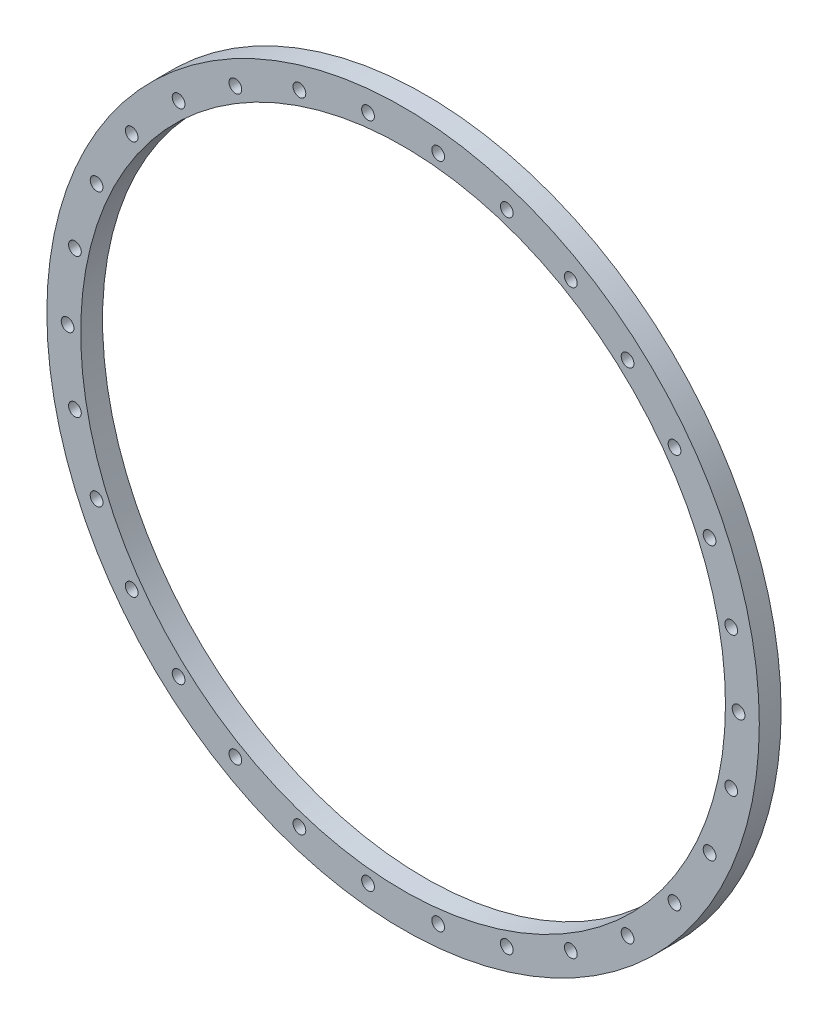
SolidWorks part; units mm, degrees
ref_plane "Plan de face" through (0, 0, 0) normal (0, 0, 1) x (1, 0, 0)
ref_plane "Plan de dessus" through (0, 0, 0) normal (0, 1, 0) x (1, 0, 0)
ref_plane "Plan de droite" through (0, 0, 0) normal (1, 0, 0) x (0, 0, -1)
sketch "Esquisse1" plane through (0, 0, 0) normal (0, 0, 1) x (1, 0, 0)
  line L0 (0, 0) -> (-461, 0) construction
  line L1 (0, 0) -> (-450.926, 95.8473) construction
  circle A0 centre (0, 0) radius 443
  circle A1 centre (0, 0) radius 489.5
  circle A2 centre (-461, 0) radius 8.75
  circle A3 centre (-450.926, 95.8473) radius 8.75
  circle A4 centre (-421.1445, 187.5056) radius 8.75
  circle A5 centre (-372.9568, 270.969) radius 8.75
  circle A6 centre (-308.4692, 342.5898) radius 8.75
  circle A7 centre (-230.5, 399.2377) radius 8.75
  circle A8 centre (-142.4568, 438.4371) radius 8.75
  circle A9 centre (-48.1876, 458.4746) radius 8.75
  circle A10 centre (48.1876, 458.4746) radius 8.75
  circle A11 centre (142.4568, 438.4371) radius 8.75
  circle A12 centre (230.5, 399.2377) radius 8.75
  circle A13 centre (308.4692, 342.5898) radius 8.75
  circle A14 centre (372.9568, 270.969) radius 8.75
  circle A15 centre (421.1445, 187.5056) radius 8.75
  circle A16 centre (450.926, 95.8473) radius 8.75
  circle A17 centre (461, 0) radius 8.75
  circle A18 centre (450.926, -95.8473) radius 8.75
  circle A19 centre (421.1445, -187.5056) radius 8.75
  circle A20 centre (372.9568, -270.969) radius 8.75
  circle A21 centre (308.4692, -342.5898) radius 8.75
  circle A22 centre (230.5, -399.2377) radius 8.75
  circle A23 centre (142.4568, -438.4371) radius 8.75
  circle A24 centre (48.1876, -458.4746) radius 8.75
  circle A25 centre (-48.1876, -458.4746) radius 8.75
  circle A26 centre (-142.4568, -438.4371) radius 8.75
  circle A27 centre (-230.5, -399.2377) radius 8.75
  circle A28 centre (-308.4692, -342.5898) radius 8.75
  circle A29 centre (-372.9568, -270.969) radius 8.75
  circle A30 centre (-421.1445, -187.5056) radius 8.75
  circle A31 centre (-450.926, -95.8473) radius 8.75
  circle A32 centre (0, 0) radius 461 construction
  point P67 (0, 0)
  dimension "D1" = 979
  dimension "D2" = 886
  dimension "D3" = 17.5
  dimension "D4" = 461
  dimension "D5" = 30
extrude "Boss.-Extru.1" add sketch "Esquisse1" along normal blind 30
